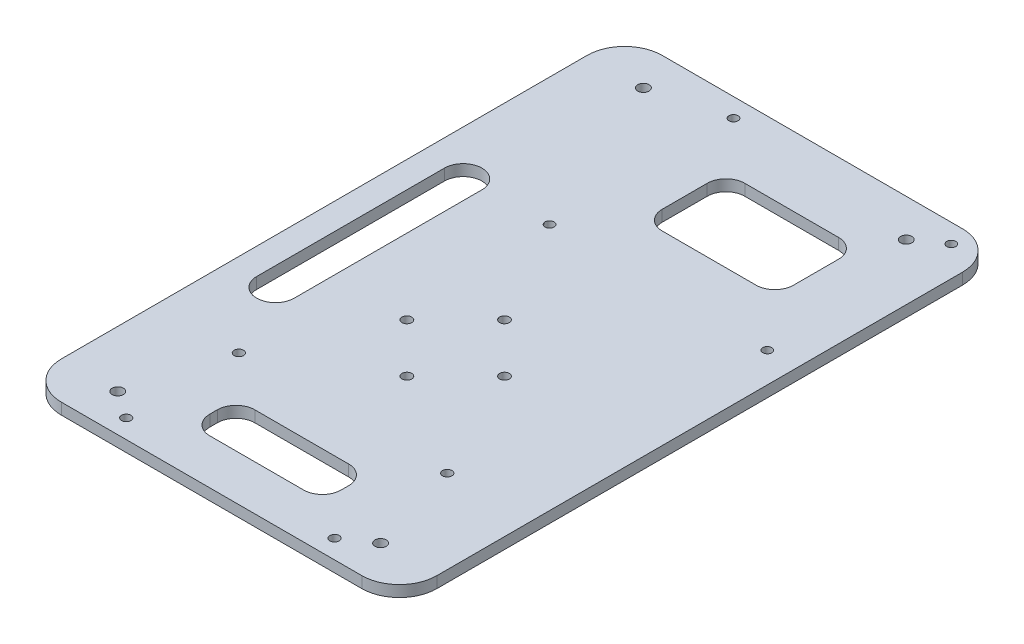
SolidWorks part; units mm, degrees
ref_plane "前视基准面" through (0, 0, 0) normal (0, 0, 1) x (1, 0, 0)
ref_plane "上视基准面" through (0, 0, 0) normal (0, 1, 0) x (1, 0, 0)
ref_plane "右视基准面" through (0, 0, 0) normal (1, 0, 0) x (0, 0, -1)
other "Configuration Table"
sketch "草图1" plane through (0, 0, 0) normal (0, 1, 0) x (1, 0, 0)
  line L0 (0, 119.0805) -> (0, -123.6398) construction
  line L1 (-50, -80) -> (50, -80)
  line L2 (-50, -80) -> (-50, 80)
  line L3 (-50, 80) -> (50, 80)
  line L4 (50, -80) -> (50, 80)
  line L5 (-50, -80) -> (50, 80) construction
  line L6 (-50, 80) -> (50, -80) construction
  line L7 (-120.6897, 0) -> (123.1034, 0) construction
  line L8 (-38, -25) -> (-38, 25) construction
  line L9 (-17.5, -68) -> (17.5, -68)
  line L10 (-17.5, -68) -> (-17.5, -56)
  line L11 (-17.5, -56) -> (17.5, -56)
  line L12 (17.5, -68) -> (17.5, -56)
  line L13 (-17.5, -68) -> (17.5, -56) construction
  line L14 (-17.5, -56) -> (17.5, -68) construction
  line L15 (-16, 75) -> (42, 75) construction
  line L16 (-16, 75) -> (-16, 26) construction
  line L17 (-16, 26) -> (42, 26) construction
  line L18 (42, 75) -> (42, 26) construction
  line L19 (-4.5, 39.5) -> (30.5, 39.5)
  line L20 (-4.5, 39.5) -> (-4.5, 61.5)
  line L21 (-4.5, 61.5) -> (30.5, 61.5)
  line L22 (30.5, 39.5) -> (30.5, 61.5)
  line L23 (-4.5, 39.5) -> (30.5, 61.5) construction
  line L24 (-4.5, 61.5) -> (30.5, 39.5) construction
  line L25 (-43, -25) -> (-43, 25)
  line L26 (-33, -25) -> (-33, 25)
  circle A0 centre (35, 70) radius 1.5
  circle A1 centre (-35, 70) radius 1.5
  circle A2 centre (-35, -70) radius 1.5
  circle A3 centre (35, -70) radius 1.5
  circle A4 centre (0, -15) radius 13 construction
  circle A5 centre (0, -2) radius 1.3
  circle A6 centre (13, -15) radius 1.3
  circle A7 centre (0, -28) radius 1.3
  circle A8 centre (-13, -15) radius 1.3
  circle A9 centre (-16, 26) radius 1.2
  circle A10 centre (42, 26) radius 1.2
  circle A11 centre (42, 75) radius 1.2
  circle A12 centre (-16, 75) radius 1.2
  circle A13 centre (-27.75, -75) radius 1.25
  circle A14 centre (27.75, -75) radius 1.25
  circle A15 centre (27.75, -45) radius 1.25
  circle A16 centre (-27.75, -45) radius 1.25
  circle A17 centre (0, -15) radius 30 construction
  arc A18 (-43, -25) -> (-33, -25) centre (-38, -25) ccw
  arc A19 (-33, 25) -> (-43, 25) centre (-38, 25) ccw
  point P0 (0, 0)
  point P31 (0, -15)
  point P33 (13, 50.5)
  point P40 (0, -62)
  point P56 (13, 75)
  point P57 (42, 50.5)
  point P60 (-38, 0)
  dimension "D1" = 140
  dimension "D2" = 70
  dimension "D5" = 3
  dimension "D6" = 15
  dimension "D7" = 26
  dimension "D8" = 2.6
  dimension "D12" = 2.4
  dimension "D14" = 49
  dimension "D16" = 16
  dimension "D22" = 5
  dimension "D24" = 30
  dimension "D25" = 2.5
  dimension "D26" = 60
  dimension "D29" = 5
  dimension "D3" = 100
  dimension "D4" = 160
  dimension "D13" = 58
  dimension "D15" = 5
  dimension "D17" = 18
  dimension "D18" = 12
  dimension "D19" = 35
  dimension "D23" = 55.5
  dimension "D27" = 35
  dimension "D28" = 22
  dimension "D30" = 12
  dimension "D31" = 50
  dimension "D10" = 2
  dimension "D11" = 2
  dimension "D20" = 2
  dimension "D21" = 2
  dimension "D9" = 4
extrude "凸台-拉伸1" add sketch "草图1" along normal blind 3
fillet "圆角1" radius 10 4 edges at (-50, 1.5, 80) (-50, 1.5, -80) (50, 1.5, -80) (50, 1.5, 80)
fillet "圆角2" radius 5 8 edges at (-17.5, 1.5, 68) (17.5, 1.5, 68) (17.5, 1.5, 56) (-17.5, 1.5, 56) (30.5, 1.5, -39.5) (30.5, 1.5, -61.5) (-4.5, 1.5, -39.5) (-4.5, 1.5, -61.5)
